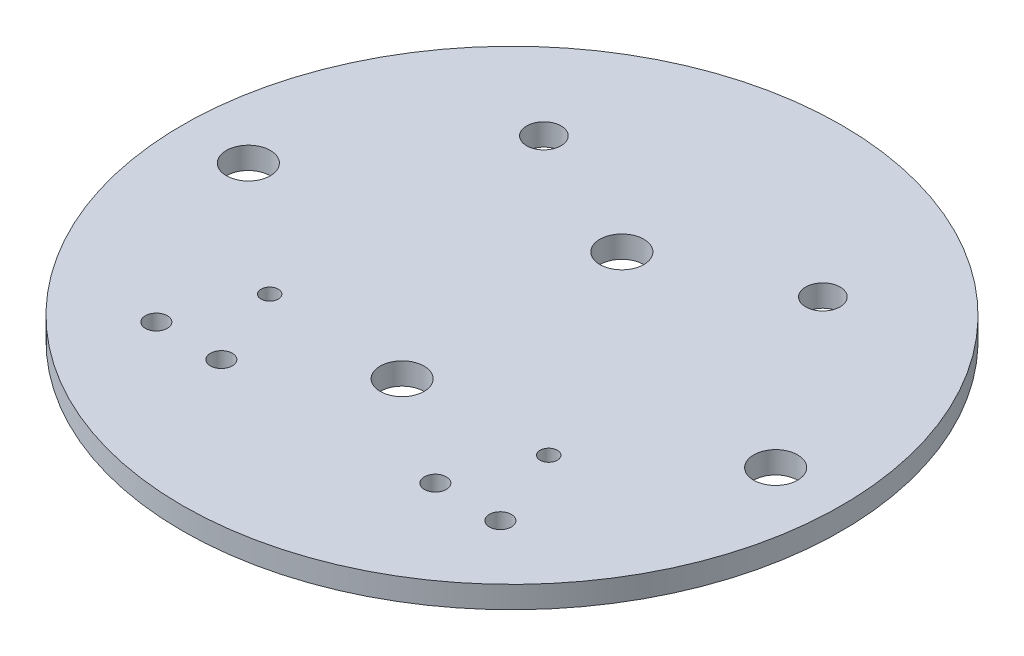
SolidWorks part; units mm, degrees
material "A-Glass Fiber"
ref_plane "Front Plane" through (0, 0, 0) normal (0, 0, 1) x (1, 0, 0)
ref_plane "Top Plane" through (0, 0, 0) normal (0, 1, 0) x (1, 0, 0)
ref_plane "Right Plane" through (0, 0, 0) normal (1, 0, 0) x (0, 0, -1)
sketch "Sketch1" plane through (0, 0, 0) normal (0, 1, 0) x (1, 0, 0)
  circle A0 centre (0, 0) radius 47.625
  dimension "D1" = 95.25
extrude "Boss-Extrude1" add sketch "Sketch1" along normal blind 3.175
extrude "Cut-Extrude1" cut sketch "Sketch2" against normal blind 263.398
sketch "Sketch2" plane through (-55.0397, 231.775, -116.0884) normal (0, 1, 0) x (-1, 0, 0)
  circle A0 centre (-93.1397, 116.0884) radius 3.175
  circle A1 centre (-16.9397, 116.0884) radius 3.175
extrude "Cut-Extrude2" cut sketch "Sketch3" against normal blind 25.4
sketch "Sketch3" plane through (-28.2644, -3.175, -82.3713) normal (0, -1, 0) x (1, 0, 0)
  circle A0 centre (28.2644, 98.2463) radius 3.175
  circle A1 centre (28.2644, 66.4963) radius 3.175
extrude "Cut-Extrude3" cut sketch "Sketch4" against normal blind 50.8
sketch "Sketch4" plane through (-28.2644, -3.175, -82.3713) normal (0, -1, 0) x (-1, 0, 0)
  circle A0 centre (-3.4041, -108.9143) radius 1.5875
  circle A1 centre (-12.8021, -108.9143) radius 1.5875
  circle A2 centre (-43.7266, -108.9143) radius 1.5875
  circle A3 centre (-53.1246, -108.9143) radius 1.5875
  circle A4 centre (-8.1031, -97.2303) radius 1.25
  circle A5 centre (-48.4256, -97.2303) radius 1.25
  point P8 (-3.4041, -105.7393)
  point P9 (-12.8021, -105.7393)
  point P12 (-43.7266, -105.7393)
  point P15 (-53.1246, -105.7393)
extrude "Cut-Extrude4" cut sketch "Sketch5" against normal blind 50.8 from surface at -3.175
sketch "Sketch5" plane through (-28.2644, -3.175, -82.3713) normal (0, -1, 0) x (1, 0, 0)
  circle A0 centre (8.1031, 57.6063) radius 1.9844
  circle A1 centre (48.4256, 57.6063) radius 1.9844
extrude "Cut-Extrude5" cut sketch "Sketch6" against normal blind 25.4
sketch "Sketch6" plane through (-28.2644, 3.175, -82.3713) normal (0, 1, 0) x (1, 0, 0)
  circle A0 centre (8.1031, -57.6063) radius 2.4892
  circle A1 centre (48.4256, -57.6063) radius 2.4892
